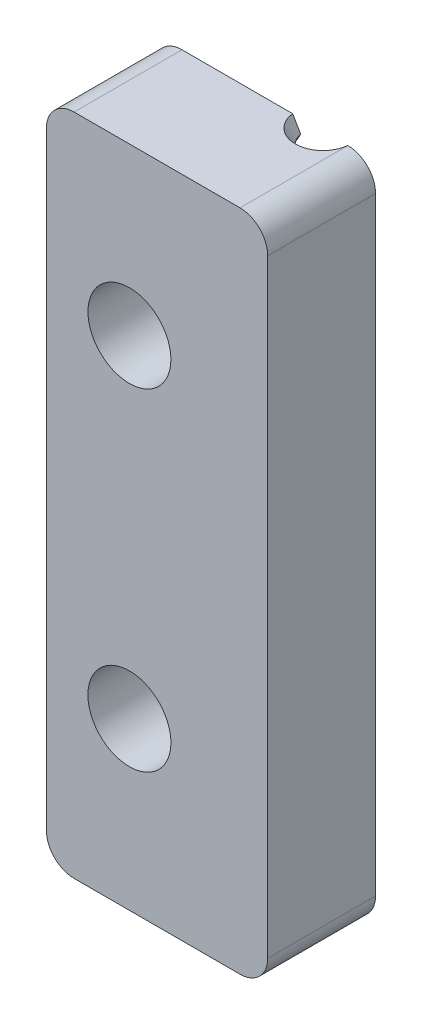
SolidWorks part; units mm, degrees
material "ABS"
ref_plane "Plan de face" through (0, 0, 0) normal (0, 0, 1) x (1, 0, 0)
ref_plane "Plan de dessus" through (0, 0, 0) normal (0, 1, 0) x (1, 0, 0)
ref_plane "Plan de droite" through (0, 0, 0) normal (1, 0, 0) x (0, 0, -1)
sketch "Esquisse1" plane through (0, 0, 0) normal (0, 1, 0) x (1, 0, 0)
  line L1 (-4, 0) -> (4, 0)
  line L2 (-4, 0) -> (-4, 3.9)
  line L3 (-4, 3.9) -> (4, 3.9)
  line L4 (4, 0) -> (4, 3.9)
  dimension "D1" = 3.9
  dimension "D2" = 8
extrude "Boss.-Extru.1" add sketch "Esquisse1" along normal mid plane 24
sketch "Esquisse2" plane through (0, 0, 0) normal (0, 0, 1) x (1, 0, 0)
  line L1 (-4, 0) -> (4, 0) construction
  line L2 (-4, 12) -> (-4, -12) construction
  line L3 (4, 12) -> (4, -12) construction
  line L4 (-4, 12) -> (4, 12) construction
  circle A0 centre (-1, 6) radius 1.5
  circle A1 centre (-1, -6) radius 1.5
  dimension "D1" = 12
  dimension "D2" = 1
  dimension "D3" = 3
  dimension "D4" = 3
  dimension "D5" = 6
extrude "Enlèv. mat.-Extru.1" cut sketch "Esquisse2" against normal through all
sketch "Esquisse3" plane through (0, 12, 0) normal (0, 1, 0) x (1, 0, 0)
  line L1 (-4, 0) -> (4, 0) construction
  circle A0 centre (2, 4) radius 1
  dimension "D1" = 2
  dimension "D2" = 2
  dimension "D3" = 4
extrude "Enlèv. mat.-Extru.2" cut sketch "Esquisse3" against normal blind 0.5 draft 30
sketch "Esquisse4" plane through (0, 11.5, 0) normal (0, 1, 0) x (1, 0, 0)
  circle A0 centre (2, 4) radius 0.7113
  arc A1 (1.2957, 3.9) -> (2.7043, 3.9) centre (2, 4) ccw construction
extrude "Enlèv. mat.-Extru.3" cut sketch "Esquisse4" against normal blind 0.5 draft 30 draft outward yes
pattern_linear "Répétition linéaire1" count 24 spacing 1 along (0, -1, 0) of "Enlèv. mat.-Extru.2", "Enlèv. mat.-Extru.3"
fillet "Congé1" radius 1 4 edges at (-4, -12, -1.95) (4, 12, -1.95) (4, -12, -1.95) (-4, 12, -1.95)
